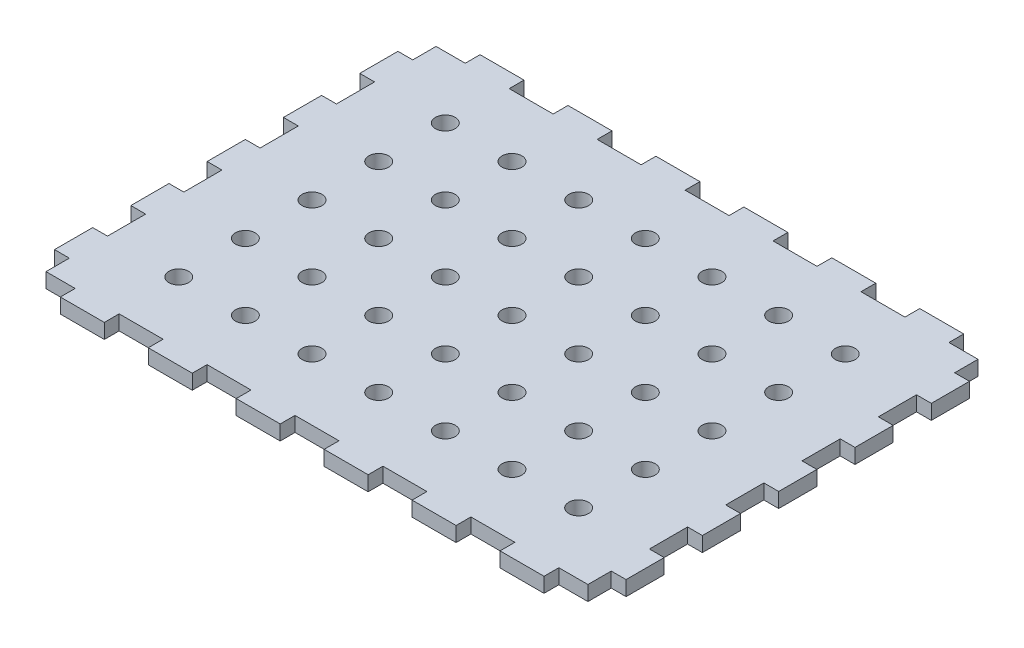
SolidWorks part; units mm, degrees
material "Balsa"
ref_plane "Front" through (0, 0, 0) normal (0, 0, 1) x (1, 0, 0)
ref_plane "Top" through (0, 0, 0) normal (0, 1, 0) x (1, 0, 0)
ref_plane "Right" through (0, 0, 0) normal (1, 0, 0) x (0, 0, -1)
sketch "Esboço1" plane through (0, 0, 0) normal (0, 1, 0) x (1, 0, 0)
  line L0 (-115.75, 85) -> (-97.75, 85) construction
  line L1 (115.75, -85) -> (-115.75, -85)
  line L2 (115.75, -85) -> (115.75, 85)
  line L3 (115.75, 85) -> (-115.75, 85)
  line L4 (-115.75, -85) -> (-115.75, 85)
  line L5 (115.75, -85) -> (-115.75, 85) construction
  line L6 (115.75, 85) -> (-115.75, -85) construction
  line L7 (-97.75, 85) -> (-97.75, 67) construction
  line L8 (-97.75, 67) -> (-115.75, 67) construction
  line L9 (115.75, -85) -> (97.75, -85) construction
  line L10 (97.75, -85) -> (97.75, -67) construction
  line L11 (97.75, -67) -> (115.75, -67) construction
  line L12 (-97.75, 67) -> (-97.75, 54) construction
  line L13 (-97.75, 67) -> (97.75, 67)
  line L14 (-97.75, 67) -> (-97.75, -67)
  line L15 (-97.75, -67) -> (97.75, -67)
  line L16 (97.75, 67) -> (97.75, -67)
  line L17 (-97.75, 54) -> (-81, 54) construction
  circle A0 centre (-81, 54) radius 4
  circle A1 centre (-54, 54) radius 4
  circle A2 centre (-27, 54) radius 4
  circle A3 centre (0, 54) radius 4
  circle A4 centre (27, 54) radius 4
  circle A5 centre (54, 54) radius 4
  circle A6 centre (81, 54) radius 4
  circle A7 centre (-54, 27) radius 4
  circle A8 centre (-27, 27) radius 4
  circle A9 centre (0, 27) radius 4
  circle A10 centre (27, 27) radius 4
  circle A11 centre (54, 27) radius 4
  circle A12 centre (81, 27) radius 4
  circle A13 centre (-54, 0) radius 4
  circle A14 centre (-27, 0) radius 4
  circle A15 centre (0, 0) radius 4
  circle A16 centre (27, 0) radius 4
  circle A17 centre (54, 0) radius 4
  circle A18 centre (81, 0) radius 4
  circle A19 centre (-54, -27) radius 4
  circle A20 centre (-27, -27) radius 4
  circle A21 centre (0, -27) radius 4
  circle A22 centre (27, -27) radius 4
  circle A23 centre (54, -27) radius 4
  circle A24 centre (81, -27) radius 4
  circle A25 centre (-54, -54) radius 4
  circle A26 centre (-27, -54) radius 4
  circle A27 centre (0, -54) radius 4
  circle A28 centre (27, -54) radius 4
  circle A29 centre (54, -54) radius 4
  circle A30 centre (81, -54) radius 4
  circle A31 centre (-81, 27) radius 4
  circle A32 centre (-81, 0) radius 4
  circle A33 centre (-81, -27) radius 4
  circle A34 centre (-81, -54) radius 4
  point P0 (0, 0)
  dimension "D7" = 7
  dimension "D1" = 231.5
  dimension "D2" = 170
  dimension "D3" = 195.5
  dimension "D4" = 134
  dimension "D5" = 13
  dimension "D6" = 16.75
  dimension "D8" = 5
extrude "Ressalto-extrusão1" add sketch "Esboço1" along normal blind 6 contours L16 L13 L14 L15 A34 A33 A32 A31 A30 A29 A28 A27 A26 A25 A24 A23 A22 A21 A20 A19 A18 A17 A16 A15 A14 A13 A12 | L4 L1 L2 L3 L13 L16 L15 L14
sketch "Esboço5" plane through (0, 0, 0) normal (0, 1, 0) x (1, 0, 0)
  line L0 (-115.75, 85) -> (-97.75, 85) construction
  line L1 (115.75, -85) -> (-115.75, -85)
  line L2 (115.75, -85) -> (115.75, 85)
  line L3 (115.75, 85) -> (-115.75, 85)
  line L4 (-115.75, -85) -> (-115.75, 85)
  line L5 (115.75, -85) -> (-115.75, 85) construction
  line L6 (115.75, 85) -> (-115.75, -85) construction
  line L7 (-97.75, 85) -> (-97.75, 67) construction
  line L8 (-97.75, 67) -> (-115.75, 67) construction
  line L9 (115.75, -85) -> (97.75, -85) construction
  line L10 (97.75, -85) -> (97.75, -67) construction
  line L11 (97.75, -67) -> (115.75, -67) construction
  line L12 (-97.75, 67) -> (-97.75, 54) construction
  line L13 (-97.75, 67) -> (97.75, 67)
  line L14 (-97.75, 67) -> (-97.75, -67)
  line L15 (-97.75, -67) -> (97.75, -67)
  line L16 (97.75, 67) -> (97.75, -67)
  line L17 (-97.75, 54) -> (-81, 54) construction
  circle A0 centre (-81, 54) radius 4
  circle A1 centre (-54, 54) radius 4
  circle A2 centre (-27, 54) radius 4
  circle A3 centre (0, 54) radius 4
  circle A4 centre (27, 54) radius 4
  circle A5 centre (54, 54) radius 4
  circle A6 centre (81, 54) radius 4
  circle A7 centre (-54, 27) radius 4
  circle A8 centre (-27, 27) radius 4
  circle A9 centre (0, 27) radius 4
  circle A10 centre (27, 27) radius 4
  circle A11 centre (54, 27) radius 4
  circle A12 centre (81, 27) radius 4
  circle A13 centre (-54, 0) radius 4
  circle A14 centre (-27, 0) radius 4
  circle A15 centre (0, 0) radius 4
  circle A16 centre (27, 0) radius 4
  circle A17 centre (54, 0) radius 4
  circle A18 centre (81, 0) radius 4
  circle A19 centre (-54, -27) radius 4
  circle A20 centre (-27, -27) radius 4
  circle A21 centre (0, -27) radius 4
  circle A22 centre (27, -27) radius 4
  circle A23 centre (54, -27) radius 4
  circle A24 centre (81, -27) radius 4
  circle A25 centre (-54, -54) radius 4
  circle A26 centre (-27, -54) radius 4
  circle A27 centre (0, -54) radius 4
  circle A28 centre (27, -54) radius 4
  circle A29 centre (54, -54) radius 4
  circle A30 centre (81, -54) radius 4
  circle A31 centre (-81, 27) radius 4
  circle A32 centre (-81, 0) radius 4
  circle A33 centre (-81, -27) radius 4
  circle A34 centre (-81, -54) radius 4
  point P0 (0, 0)
  dimension "D7" = 7
  dimension "D1" = 231.5
  dimension "D2" = 170
  dimension "D3" = 195.5
  dimension "D4" = 134
  dimension "D5" = 13
  dimension "D6" = 16.75
  dimension "D8" = 5
sketch "Esboço6" plane through (0, 0, 0) normal (0, -1, 0) x (1, 0, 0)
  line L0 (115.75, 85) -> (-115.75, 85) construction
  line L1 (-115.75, 85) -> (-97.9423, 85)
  line L2 (-80.13, 85) -> (-62.3223, 85)
  line L3 (-115.75, 85) -> (-97.9423, 85)
  line L4 (-115.75, 85) -> (-115.75, 79)
  line L5 (-115.75, 79) -> (-97.9423, 79)
  line L6 (-97.9423, 85) -> (-97.9423, 79)
  line L7 (-80.13, 85) -> (-62.3223, 85)
  line L8 (-80.13, 85) -> (-80.13, 79)
  line L9 (-80.13, 79) -> (-62.3223, 79)
  line L10 (-62.3223, 85) -> (-62.3223, 79)
  line L11 (-44.51, 85) -> (-26.7023, 85)
  line L12 (-44.51, 85) -> (-26.7023, 85)
  line L13 (-44.51, 85) -> (-44.51, 79)
  line L14 (-44.51, 79) -> (-26.7023, 79)
  line L15 (-26.7023, 85) -> (-26.7023, 79)
  line L16 (-8.89, 85) -> (8.9177, 85)
  line L17 (-8.89, 85) -> (8.9177, 85)
  line L18 (-8.89, 85) -> (-8.89, 79)
  line L19 (-8.89, 79) -> (8.9177, 79)
  line L20 (8.9177, 85) -> (8.9177, 79)
  line L21 (26.73, 85) -> (44.5377, 85)
  line L22 (26.73, 85) -> (44.5377, 85)
  line L23 (26.73, 85) -> (26.73, 79)
  line L24 (26.73, 79) -> (44.5377, 79)
  line L25 (44.5377, 85) -> (44.5377, 79)
  line L26 (62.35, 85) -> (80.1577, 85)
  line L27 (62.35, 85) -> (80.1577, 85)
  line L28 (62.35, 85) -> (62.35, 79)
  line L29 (62.35, 79) -> (80.1577, 79)
  line L30 (80.1577, 85) -> (80.1577, 79)
  line L31 (97.97, 85) -> (115.7777, 85)
  line L32 (97.97, 85) -> (115.7777, 85)
  line L33 (97.97, 85) -> (97.97, 79)
  line L34 (97.97, 79) -> (115.7777, 79)
  line L35 (115.7777, 85) -> (115.7777, 79)
  line L37 (-115.75, -79) -> (-97.9423, -79)
  line L38 (-80.13, -79) -> (-62.3223, -79)
  line L39 (-115.75, -79) -> (-97.9423, -79)
  line L40 (-115.75, -79) -> (-115.75, -85)
  line L41 (-115.75, -85) -> (-97.9423, -85)
  line L42 (-97.9423, -79) -> (-97.9423, -85)
  line L43 (-80.13, -79) -> (-62.3223, -79)
  line L44 (-80.13, -79) -> (-80.13, -85)
  line L45 (-80.13, -85) -> (-62.3223, -85)
  line L46 (-62.3223, -79) -> (-62.3223, -85)
  line L47 (-44.51, -79) -> (-26.7023, -79)
  line L48 (-44.51, -79) -> (-26.7023, -79)
  line L49 (-44.51, -79) -> (-44.51, -85)
  line L50 (-44.51, -85) -> (-26.7023, -85)
  line L51 (-26.7023, -79) -> (-26.7023, -85)
  line L52 (-8.89, -79) -> (8.9177, -79)
  line L53 (-8.89, -79) -> (8.9177, -79)
  line L54 (-8.89, -79) -> (-8.89, -85)
  line L55 (-8.89, -85) -> (8.9177, -85)
  line L56 (8.9177, -79) -> (8.9177, -85)
  line L57 (26.73, -79) -> (44.5377, -79)
  line L58 (26.73, -79) -> (44.5377, -79)
  line L59 (26.73, -79) -> (26.73, -85)
  line L60 (26.73, -85) -> (44.5377, -85)
  line L61 (44.5377, -79) -> (44.5377, -85)
  line L62 (62.35, -79) -> (80.1577, -79)
  line L63 (62.35, -79) -> (80.1577, -79)
  line L64 (62.35, -79) -> (62.35, -85)
  line L65 (62.35, -85) -> (80.1577, -85)
  line L66 (80.1577, -79) -> (80.1577, -85)
  line L67 (97.97, -79) -> (115.7777, -79)
  line L68 (97.97, -79) -> (115.7777, -79)
  line L69 (97.97, -79) -> (97.97, -85)
  line L70 (97.97, -85) -> (115.7777, -85)
  line L71 (115.7777, -79) -> (115.7777, -85)
  line M109 (-115.75, 85) -> (-115.75, -85)
  line M110 (-115.75, -85) -> (115.75, -85)
  line M111 (115.75, -85) -> (115.75, 85)
  line M112 (115.75, 85) -> (-115.75, 85)
  dimension "D1" = 17.8077
  dimension "D2" = 6
  dimension "D4" = 2
  dimension "D3" = 7
extrude "Corte-extrusão1" cut sketch "Esboço6" against normal blind 6 contours L6 L5 M112 M109 | L10 L8 L9 M112 | L15 L13 L14 M112 | L20 L18 L19 M112 | L25 L23 L24 M112 | L30 L28 L29 M112 | L33 L34 M111 M112 | L67 L69 M110 M111 | L66 L62 L64 M110 | L61 L57 L59 M110 | L56 L52 L54 M110 | L51 L47 L49 M110 | L46 L38 L44 M110 | L42 L37 M109 M110
sketch "Esboço7" plane through (0, 0, 0) normal (0, -1, 0) x (1, 0, 0)
  line L0 (109.75, -85) -> (115.75, -85)
  line L1 (-115.75, -85) -> (-109.75, -85)
  line L2 (-115.75, -85) -> (-115.75, -69.5455)
  line L3 (-115.75, -69.5455) -> (-109.75, -69.5455)
  line L4 (-109.75, -85) -> (-109.75, -69.5455)
  line L5 (109.75, -85) -> (109.75, -69.5455)
  line L6 (109.75, -69.5455) -> (115.75, -69.5455)
  line L7 (115.75, -85) -> (115.75, -69.5455)
  line L8 (109.75, -54.09) -> (115.75, -54.09)
  line L9 (109.75, -54.09) -> (109.75, -38.6355)
  line L10 (109.75, -38.6355) -> (115.75, -38.6355)
  line L11 (115.75, -54.09) -> (115.75, -38.6355)
  line L12 (109.75, -23.18) -> (115.75, -23.18)
  line L13 (109.75, -23.18) -> (109.75, -7.7255)
  line L14 (109.75, -7.7255) -> (115.75, -7.7255)
  line L15 (115.75, -23.18) -> (115.75, -7.7255)
  line L16 (109.75, 7.73) -> (115.75, 7.73)
  line L17 (109.75, 7.73) -> (109.75, 23.1845)
  line L18 (109.75, 23.1845) -> (115.75, 23.1845)
  line L19 (115.75, 7.73) -> (115.75, 23.1845)
  line L20 (109.75, 38.64) -> (115.75, 38.64)
  line L21 (109.75, 38.64) -> (109.75, 54.0945)
  line L22 (109.75, 54.0945) -> (115.75, 54.0945)
  line L23 (115.75, 38.64) -> (115.75, 54.0945)
  line L24 (109.75, 69.55) -> (115.75, 69.55)
  line L25 (109.75, 69.55) -> (109.75, 85.0045)
  line L26 (109.75, 85.0045) -> (115.75, 85.0045)
  line L27 (115.75, 69.55) -> (115.75, 85.0045)
  line L28 (-115.75, -54.09) -> (-109.75, -54.09)
  line L29 (-115.75, -54.09) -> (-115.75, -38.6355)
  line L30 (-115.75, -38.6355) -> (-109.75, -38.6355)
  line L31 (-109.75, -54.09) -> (-109.75, -38.6355)
  line L32 (-115.75, -23.18) -> (-109.75, -23.18)
  line L33 (-115.75, -23.18) -> (-115.75, -7.7255)
  line L34 (-115.75, -7.7255) -> (-109.75, -7.7255)
  line L35 (-109.75, -23.18) -> (-109.75, -7.7255)
  line L36 (-115.75, 7.73) -> (-109.75, 7.73)
  line L37 (-115.75, 7.73) -> (-115.75, 23.1845)
  line L38 (-115.75, 23.1845) -> (-109.75, 23.1845)
  line L39 (-109.75, 7.73) -> (-109.75, 23.1845)
  line L40 (-115.75, 38.64) -> (-109.75, 38.64)
  line L41 (-115.75, 38.64) -> (-115.75, 54.0945)
  line L42 (-115.75, 54.0945) -> (-109.75, 54.0945)
  line L43 (-109.75, 38.64) -> (-109.75, 54.0945)
  line L44 (-115.75, 69.55) -> (-109.75, 69.55)
  line L45 (-115.75, 69.55) -> (-115.75, 85.0045)
  line L46 (-115.75, 85.0045) -> (-109.75, 85.0045)
  line L47 (-109.75, 69.55) -> (-109.75, 85.0045)
  dimension "D1" = 6
  dimension "D2" = 15.4545
  dimension "D3" = 2
  dimension "D4" = 6
extrude "Corte-extrusão2" cut sketch "Esboço7" against normal up to next
